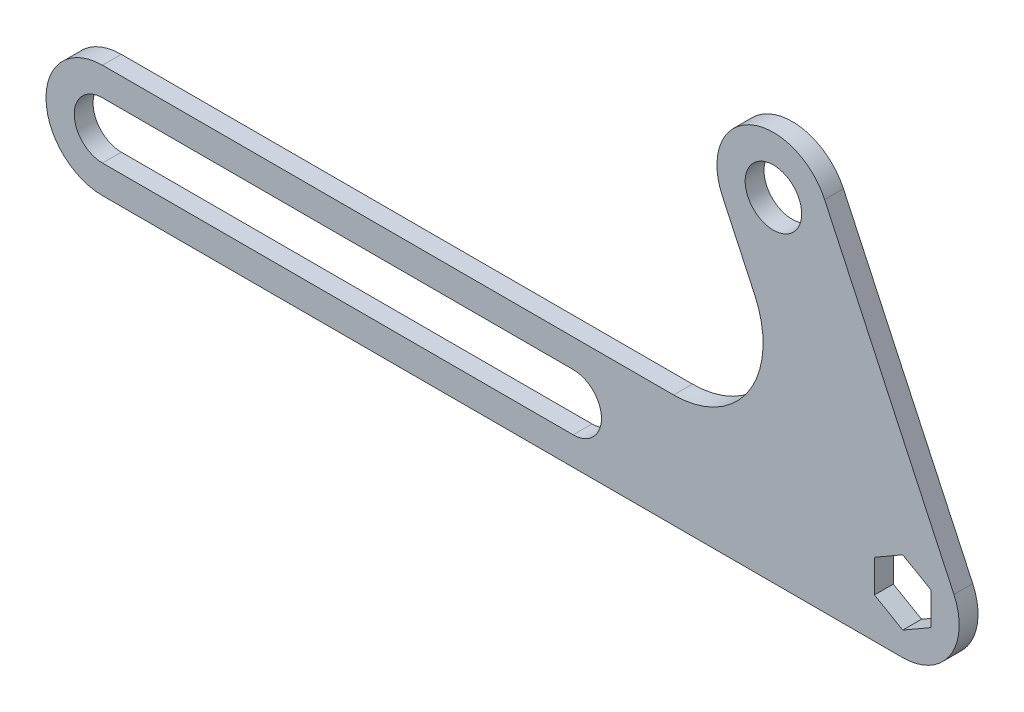
SolidWorks part; units mm, degrees
ref_plane "Front Plane" through (0, 0, 0) normal (0, 0, 1) x (1, 0, 0)
ref_plane "Top Plane" through (0, 0, 0) normal (0, 1, 0) x (1, 0, 0)
ref_plane "Right Plane" through (0, 0, 0) normal (1, 0, 0) x (0, 0, -1)
sketch "Sketch1" plane through (0, 0, 0) normal (0, 0, 1) x (1, 0, 0)
  line L0 (0, 0) -> (170, 0)
  line L1 (180.8757, 17.0714) -> (153.4055, 75.9814)
  line L2 (131.6541, 65.8386) -> (138.5596, 51.0297)
  line L3 (121.3397, 24) -> (0, 24)
  line L4 (0, 12) -> (100, 12) construction
  line L5 (0, 18) -> (100, 18)
  line L6 (0, 6) -> (100, 6)
  line L7 (100, 12) -> (170, 12) construction
  line L14 (170, 12) -> (142.5298, 70.91) construction
  line L15 (131.6541, 65.8386) -> (153.4055, 75.9814) construction
  line L16 (170, 18.9282) -> (164, 15.4641)
  line L17 (164, 15.4641) -> (164, 8.5359)
  line L18 (164, 8.5359) -> (170, 5.0718)
  line L19 (170, 5.0718) -> (176, 8.5359)
  line L20 (176, 8.5359) -> (176, 15.4641)
  line L21 (176, 15.4641) -> (170, 18.9282)
  arc A1 (153.4055, 75.9814) -> (131.6541, 65.8386) centre (142.5298, 70.91) ccw
  arc A2 (138.5596, 51.0297) -> (121.3397, 24) centre (121.3397, 43) cw
  arc A3 (0, 24) -> (0, 0) centre (0, 12) ccw
  arc A4 (0, 18) -> (0, 6) centre (0, 12) ccw
  arc A5 (100, 6) -> (100, 18) centre (100, 12) ccw
  circle A6 centre (170, 12) radius 6 construction
  circle A7 centre (142.5298, 70.91) radius 6
  arc A8 (170, 0) -> (180.8757, 17.0714) centre (170, 12) ccw
  point P13 (50, 12)
  dimension "D3" = 12
  dimension "D5" = 12
  dimension "D6" = 19
  dimension "D7" = 12
  dimension "D10" = 6
  dimension "D12" = 12
  dimension "D2" = 100
  dimension "D4" = 65
  dimension "D8" = 12
  dimension "D9" = 170
  dimension "D11" = 65
extrude "Boss-Extrude1" add sketch "Sketch1" along normal blind 4
equation "\"D2@Sketch1\"=\"D9@Sketch1\"-70"
